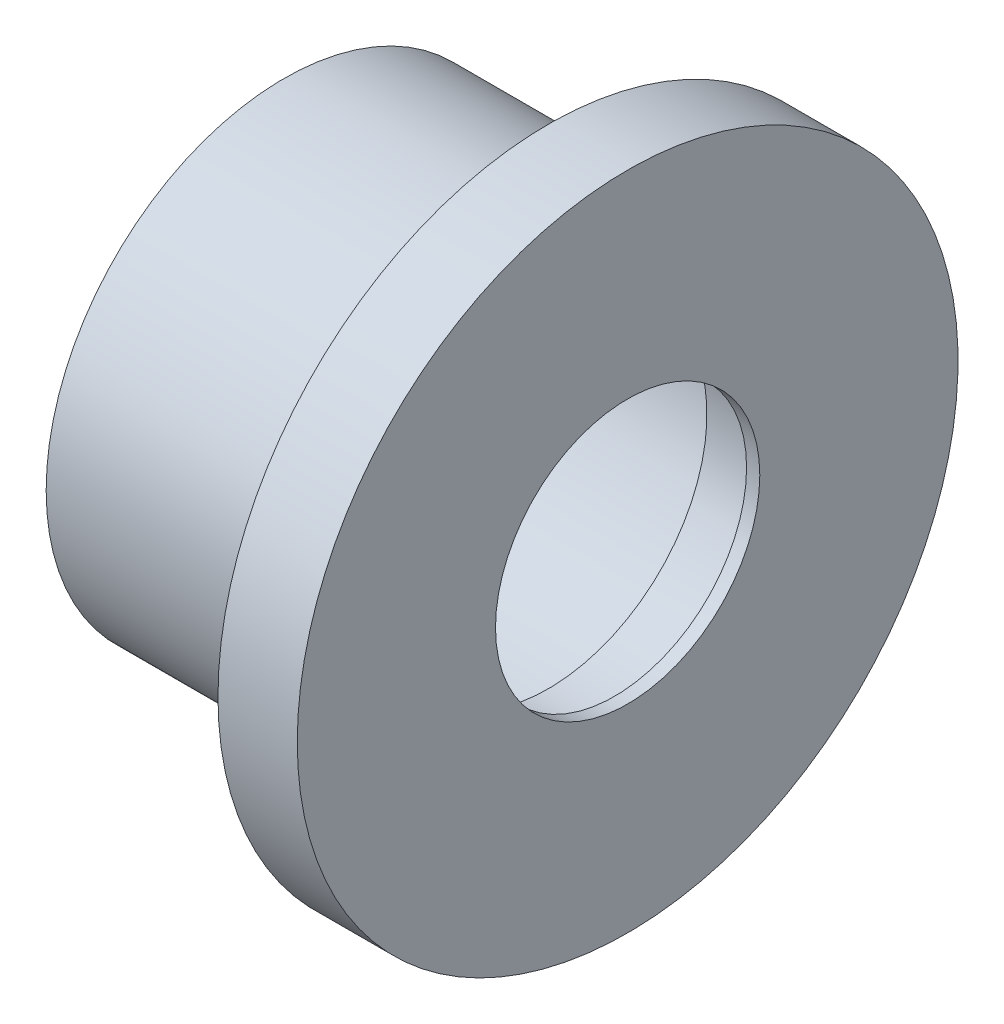
SolidWorks part; units mm, degrees
ref_plane "Front Plane" through (0, 0, 0) normal (0, 0, 1) x (1, 0, 0)
ref_plane "Top Plane" through (0, 0, 0) normal (0, 1, 0) x (1, 0, 0)
ref_plane "Right Plane" through (0, 0, 0) normal (1, 0, 0) x (0, 0, -1)
sketch "Sketch1" plane through (0, 0, 0) normal (0, 0, 1) x (1, 0, 0)
  line L0 (-42.8096, 0) -> (42.8096, 0) construction
  line L1 (-1, 12) -> (-6, 12)
  line L2 (-6, 12) -> (-6, 16)
  line L3 (-6, 16) -> (-26, 16)
  line L4 (-26, 16) -> (-26, 18)
  line L6 (0, 25) -> (0, 10)
  line L9 (0, 10) -> (-1, 10)
  line L10 (-1, 10) -> (-1, 12)
  line L11 (-26, 18) -> (-6, 18)
  line L12 (-6, 18) -> (-6, 25)
  line L13 (-6, 25) -> (0, 25)
  point P3 (0, 0)
  point P4 (0, 0)
  point P15 (42.8096, 0)
  dimension "D1" = 2
  dimension "D2" = 6
  dimension "D3" = 5
  dimension "D4" = 24
  dimension "D5" = 32
  dimension "D6" = 2
  dimension "D7" = 50
  dimension "D8" = 6
  dimension "D9" = 20
revolve "Revolve1" add sketch "Sketch1" angle 360 about L0
